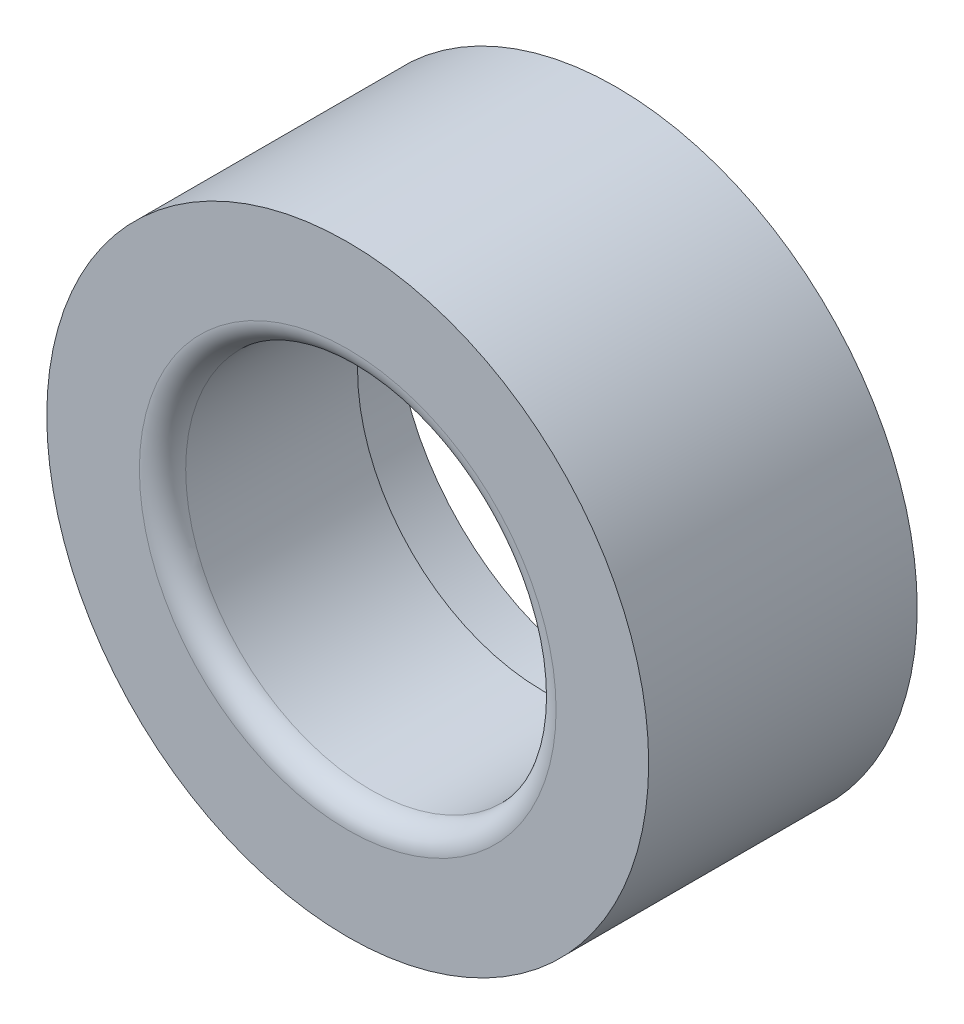
SolidWorks part; units mm, degrees
ref_plane "Front Plane" through (0, 0, 0) normal (0, 0, 1) x (1, 0, 0)
ref_plane "Top Plane" through (0, 0, 0) normal (0, 1, 0) x (1, 0, 0)
ref_plane "Right Plane" through (0, 0, 0) normal (1, 0, 0) x (0, 0, -1)
sketch "Sketch1" plane through (0, 0, 0) normal (0, 0, 1) x (1, 0, 0)
  circle A0 centre (85.2065, -1.764) radius 6.5
  dimension "D1" = 13
extrude "Boss-Extrude1" add sketch "Sketch1" along normal blind 5.8
sketch "Sketch2" plane through (0, 0, 5.8) normal (0, 0, 1) x (1, 0, 0)
  circle A0 centre (85.2065, -1.764) radius 4
  dimension "D1" = 8
extrude "Cut-Extrude1" cut sketch "Sketch2" against normal through all
sketch "Sketch3" plane through (0, 0, 0) normal (0, 0, -1) x (-1, 0, 0)
  circle A0 centre (-85.2065, -1.764) radius 4.775
  dimension "D1" = 9.55
fillet "Fillet1" radius 0.5 1 edges at (89.2065, -1.764, 5.8)
extrude "Cut-Extrude2" cut sketch "Sketch3" against normal blind 1.5875
